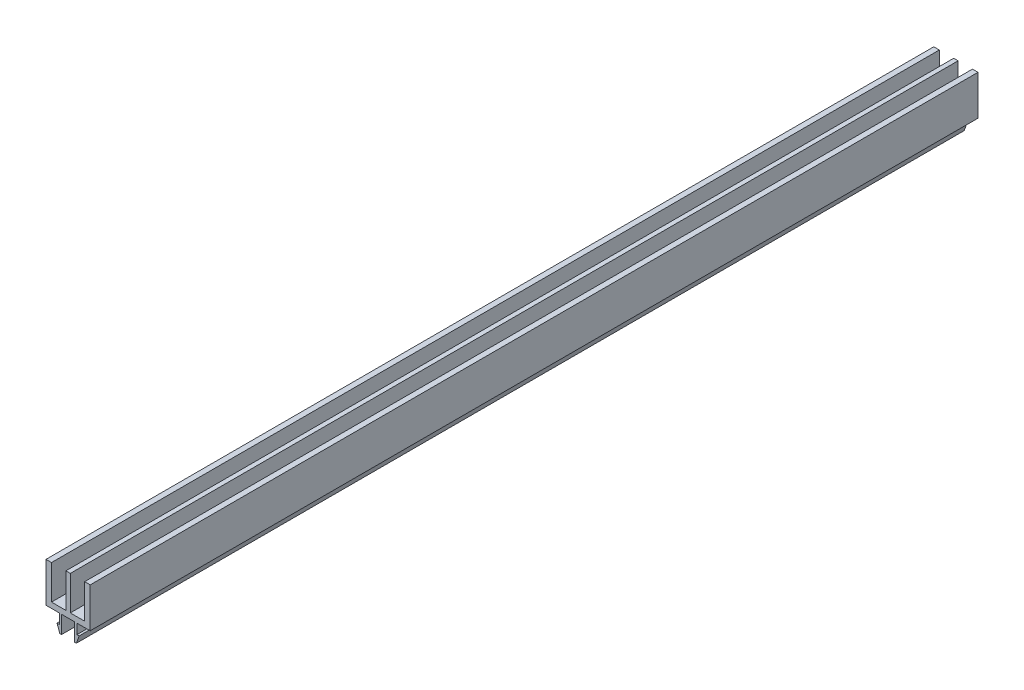
SolidWorks part; units mm, degrees
ref_plane "Plan de face" through (0, 0, 0) normal (0, 0, 1) x (1, 0, 0)
ref_plane "Plan de dessus" through (0, 0, 0) normal (0, 1, 0) x (1, 0, 0)
ref_plane "Plan de droite" through (0, 0, 0) normal (1, 0, 0) x (0, 0, -1)
ref_plane "Plan1" through (0, 0, 50) normal (0, 0, 1) x (1, 0, 0)
sketch "Esquisse1" plane through (0, 0, 50) normal (0, 0, 1) x (1, 0, 0)
  line L0 (-1, 2.5) -> (-7.5, 2.5)
  line L1 (-7.5, 2.5) -> (-7.5, 18)
  line L2 (-7.5, 18) -> (-10, 18)
  line L3 (-10, 18) -> (-10, 0)
  line L4 (-10, 0) -> (-4, 0)
  line L5 (-4, 0) -> (-4, -4.5)
  line L6 (-4, -4.5) -> (-5, -4.5)
  line L7 (-5, -4.5) -> (-3.75, -8)
  line L8 (-3.75, -8) -> (-3, -8)
  line L9 (-3, -8) -> (-3, 0)
  line L10 (-3, 0) -> (3, 0)
  line L11 (3, 0) -> (3, -8)
  line L12 (3, -8) -> (3.75, -8)
  line L13 (3.75, -8) -> (5, -4.5)
  line L14 (5, -4.5) -> (4, -4.5)
  line L15 (4, -4.5) -> (4, 0)
  line L16 (4, 0) -> (10, 0)
  line L17 (10, 0) -> (10, 18)
  line L18 (10, 18) -> (7.5, 18)
  line L19 (7.5, 18) -> (7.5, 2.5)
  line L20 (7.5, 2.5) -> (1, 2.5)
  line L21 (1, 2.5) -> (1, 18)
  line L22 (1, 18) -> (-1, 18)
  line L23 (-1, 18) -> (-1, 2.5)
extrude "Boss.-Extru.1" add sketch "Esquisse1" against normal blind 401.71
